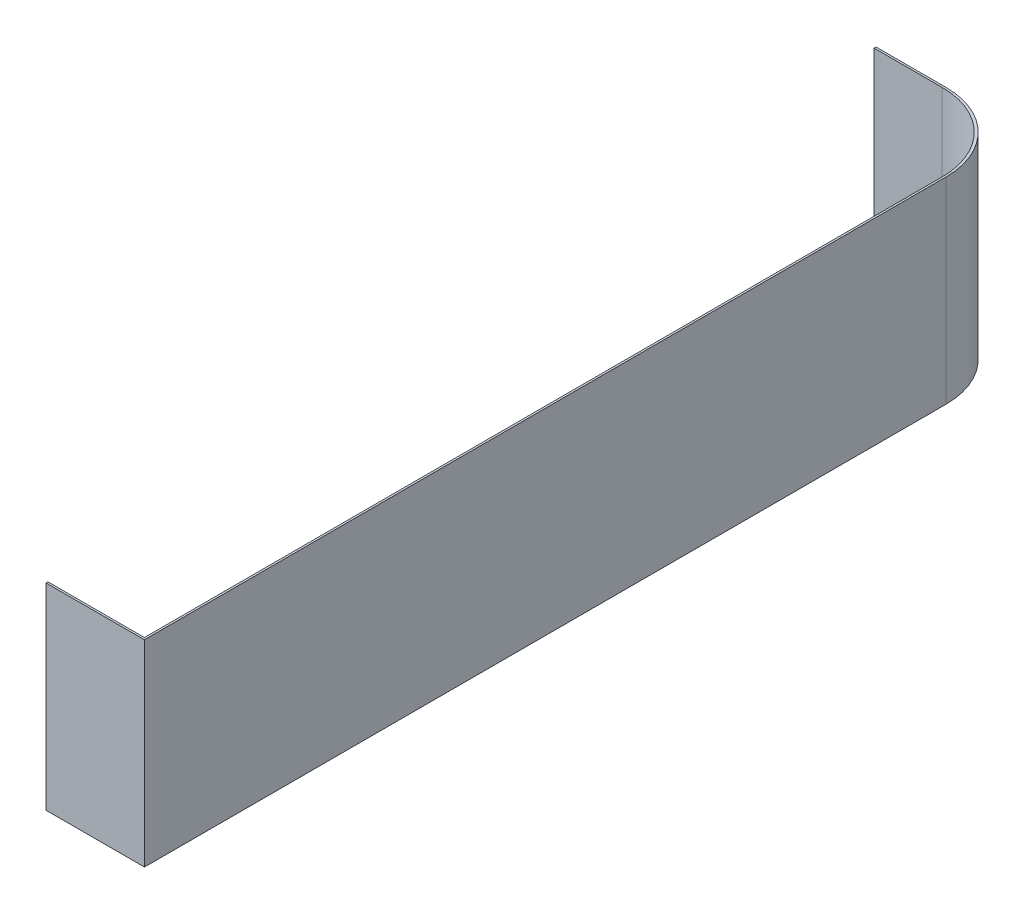
SolidWorks part; units mm, degrees
material "Copper"
ref_plane "Front Plane" through (0, 0, 0) normal (0, 0, 1) x (1, 0, 0)
ref_plane "Top Plane" through (0, 0, 0) normal (0, 1, 0) x (1, 0, 0)
ref_plane "Right Plane" through (0, 0, 0) normal (1, 0, 0) x (0, 0, -1)
sketch "Sketch1" plane through (0, 0, 0) normal (0, 1, 0) x (1, 0, 0)
  line L0 (0, 0) -> (0, -0.5)
  line L1 (0, -0.5) -> (37.5999, -0.5)
  line L2 (37.5999, -0.5) -> (37.5999, -226.3634)
  line L3 (37.5999, -226.3634) -> (12.6999, -226.3634)
  line L4 (12.6999, -226.3634) -> (12.6999, -226.8634)
  line L5 (12.6999, -226.8634) -> (38.0999, -226.8634)
  line L6 (38.0999, -226.8634) -> (38.0999, 0)
  line L7 (38.0999, 0) -> (0, 0)
  line L8 (37.5999, -0.5) -> (38.0999, -0.5) construction
  point P6 (12.6999, -68.5848)
  point P10 (66.3821, -226.3634)
  point P12 (-0.1157, 0)
  dimension "D1" = 12.6999
  dimension "D2" = 226.8634
  dimension "D3" = 0.5
  dimension "D4" = 25.4
extrude "Boss-Extrude1" add sketch "Sketch1" along normal blind 50.8
fillet "Fillet1" radius 20 2 edges at (37.5999, 25.4, 0.5) (38.0999, 25.4, 0)
